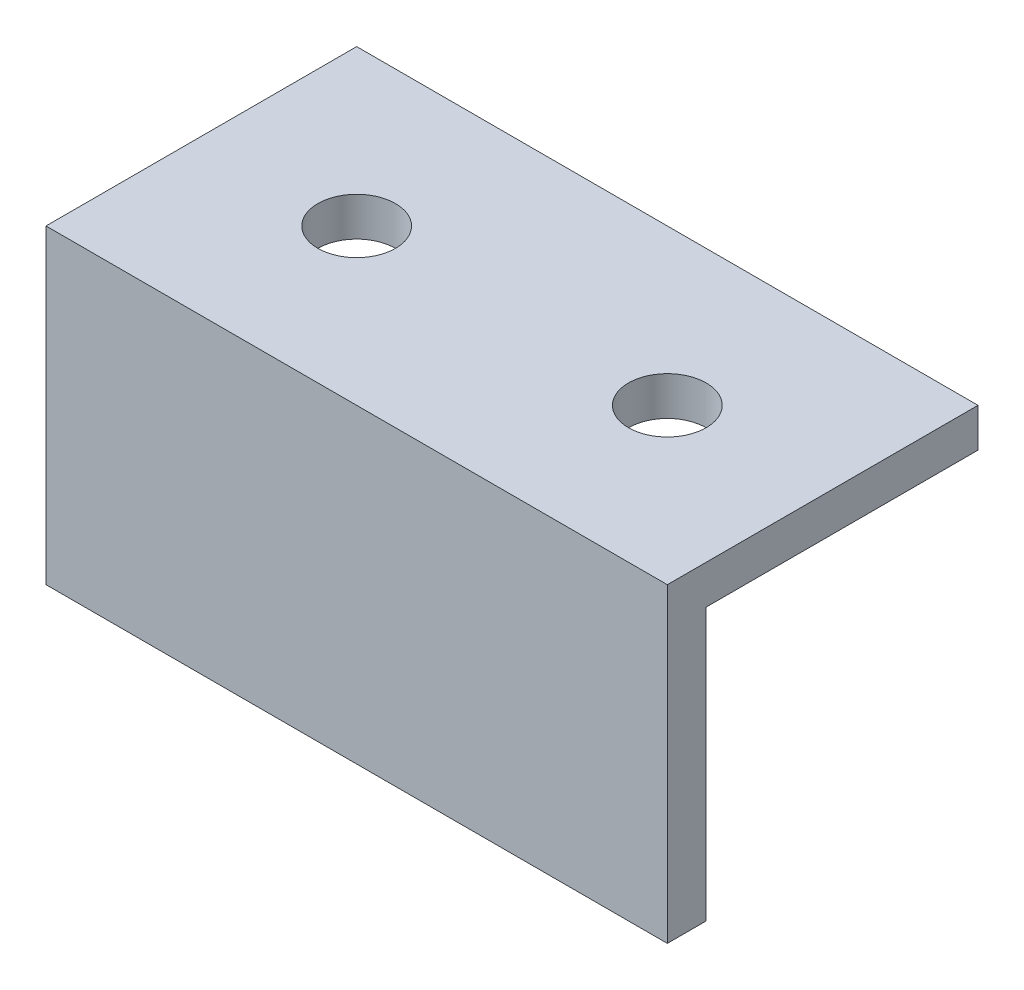
SolidWorks part; units mm, degrees
material "6061 Alloy"
ref_plane "Front Plane" through (0, 0, 0) normal (0, 0, 1) x (1, 0, 0)
ref_plane "Top Plane" through (0, 0, 0) normal (0, 1, 0) x (1, 0, 0)
ref_plane "Right Plane" through (0, 0, 0) normal (1, 0, 0) x (0, 0, -1)
sketch "Sketch1" plane through (0, 0, 0) normal (1, 0, 0) x (0, 0, -1)
  line L0 (0, 0) -> (0, 12.7)
  line L1 (0, 12.7) -> (12.7, 12.7)
  line L2 (12.7, 12.7) -> (12.7, 11.1125)
  line L3 (12.7, 11.1125) -> (1.5875, 11.1125)
  line L4 (1.5875, 11.1125) -> (1.5875, 0)
  line L5 (1.5875, 0) -> (0, 0)
  dimension "width" = 12.7
  dimension "thickness" = 1.5875
extrude "Extrude1" add sketch "Sketch1" along normal blind 25.4
sketch "Sketch2" plane through (0, 12.7, 0) normal (0, 1, 0) x (1, 0, 0)
  line L0 (0, 12.7) -> (0, 0) construction
  line L1 (25.4, 0) -> (0, 0) construction
  circle A0 centre (19.05, 6.35) radius 1.5875
  circle A1 centre (6.35, 6.35) radius 1.5875
  dimension "D1" = 12.7
  dimension "hole_dia" = 3.175
  dimension "D2" = 6.35
  dimension "D3" = 6.35
  dimension "D4" = 6.35
extrude "Extrude2" cut sketch "Sketch2" against normal up to surface (1.5875 mm away) up to face at (12.7, 11.1125, -7.1437)
equation "\"D3@Sketch2\" = \"width\"/2"
equation "\"D4@Sketch2\" = \"width\"/2"
